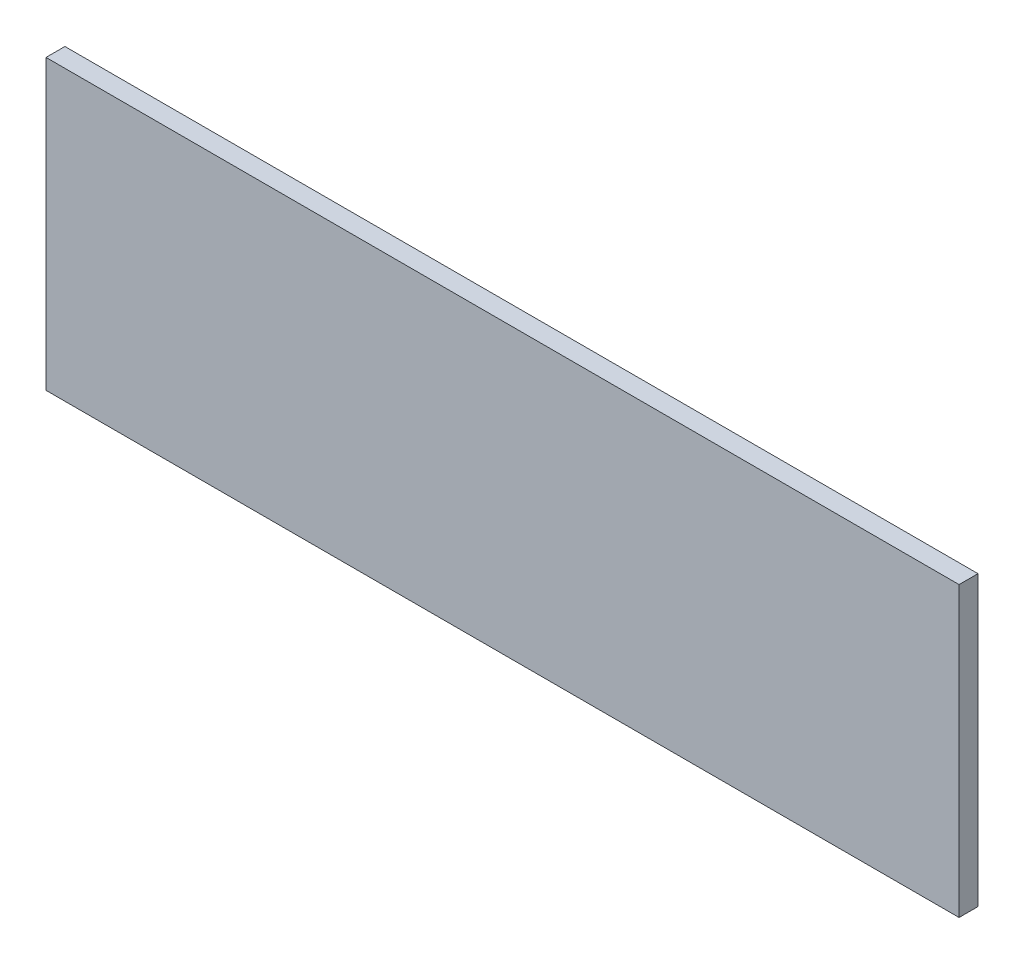
SolidWorks part; units mm, degrees
ref_plane "Alzado" through (0, 0, 0) normal (0, 0, 1) x (1, 0, 0)
ref_plane "Planta" through (0, 0, 0) normal (0, 1, 0) x (1, 0, 0)
ref_plane "Vista lateral" through (0, 0, 0) normal (1, 0, 0) x (0, 0, -1)
sketch "Croquis1" plane through (0, 0, 0) normal (0, 0, 1) x (1, 0, 0)
  line L0 (0, -55) -> (0, 55) construction
  line L1 (-24.13, 7.62) -> (24.13, 7.62)
  line L2 (-24.13, 7.62) -> (-24.13, -7.62)
  line L3 (-24.13, -7.62) -> (24.13, -7.62)
  line L4 (24.13, 7.62) -> (24.13, -7.62)
  line L5 (55, 0) -> (-55, 0) construction
  point P4 (-24.13, 0)
  point P5 (0, 7.62)
  dimension "D1" = 15.24
  dimension "D2" = 48.26
extrude "Saliente-Extruir1" add sketch "Croquis1" along normal mid plane 1
